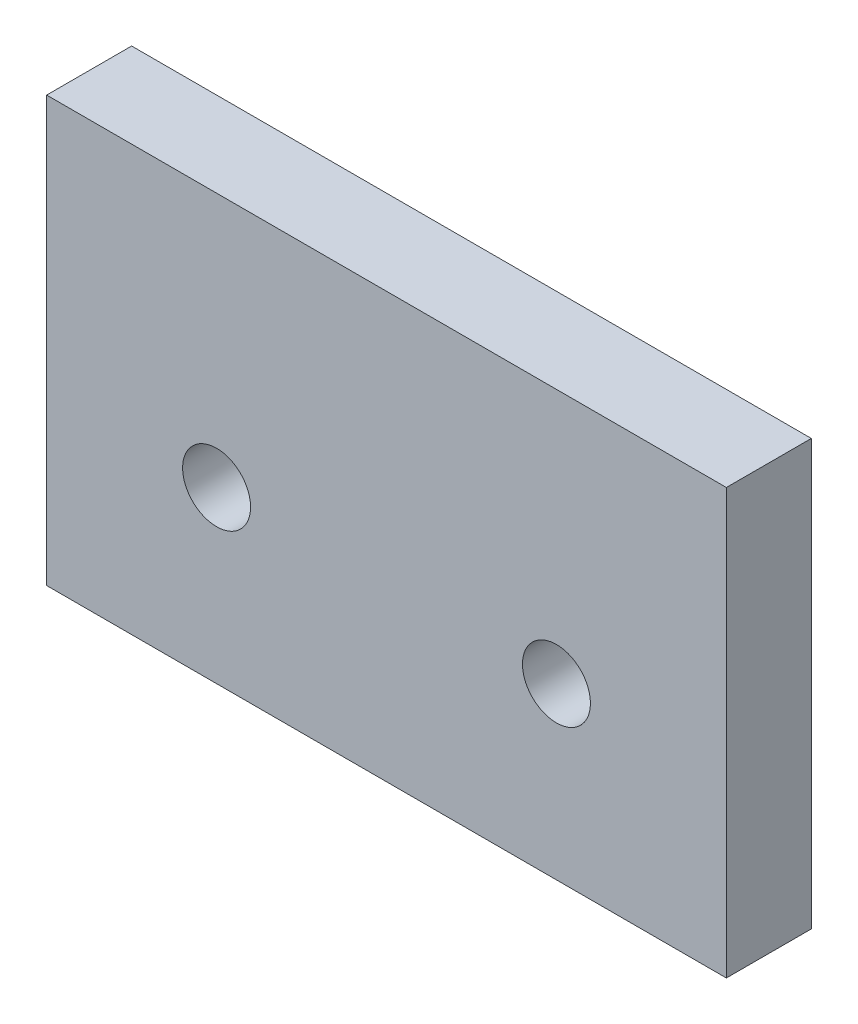
SolidWorks part; units mm, degrees
ref_plane "Front Plane" through (0, 0, 0) normal (0, 0, 1) x (1, 0, 0)
ref_plane "Top Plane" through (0, 0, 0) normal (0, 1, 0) x (1, 0, 0)
ref_plane "Right Plane" through (0, 0, 0) normal (1, 0, 0) x (0, 0, -1)
sketch "Sketch1" plane through (0, 0, 0) normal (1, 0, 0) x (0, 0, -1)
  line L0 (0, 0) -> (0, 12.7)
  line L1 (0, 0) -> (10.668, 0)
  line L2 (-3.175, -3.175) -> (10.668, -3.175)
  line L3 (-3.175, -3.175) -> (-3.175, 12.7)
  line L4 (-3.175, 12.7) -> (0, 12.7)
  line L5 (10.668, 0) -> (10.668, -3.175)
  dimension "D1" = 12.7
  dimension "D2" = 10.668
  dimension "D3" = 3.175
extrude "Boss-Extrude1" add sketch "Sketch1" along normal blind 25.4
sketch "Sketch2" plane through (0, 0, 3.175) normal (0, 0, 1) x (1, 0, 0)
  line L0 (25.4, 12.7) -> (25.4, -3.175) construction
  line L1 (25.4, 0) -> (0, 0) construction
  line L2 (25.4, 0) -> (0, 0) construction
  line L3 (0, 12.7) -> (0, -3.175) construction
  circle A0 centre (6.35, 3.175) radius 1.27
  circle A1 centre (19.05, 3.175) radius 1.27
  dimension "D2" = 2.54
  dimension "D4" = 2.54
  dimension "D1" = 6.35
  dimension "D3" = 3.175
  dimension "D5" = 3.175
  dimension "D6" = 6.35
extrude "Cut-Extrude1" cut sketch "Sketch2" against normal blind 25.4
sketch "Sketch3" plane through (0, 0, -10.668) normal (0, 0, -1) x (-1, 0, 0)
  line L4 (0, -3.175) -> (0, 0)
  line L5 (0, 0) -> (-25.4, 0)
  line L6 (-25.4, 0) -> (-25.4, -3.175)
  line L7 (-25.4, -3.175) -> (0, -3.175)
  line L8 (0, -3.175) -> (0, 0)
  line L9 (0, 0) -> (-25.4, 0)
  line L10 (-25.4, 0) -> (-25.4, -3.175)
  line L11 (-25.4, -3.175) -> (0, -3.175)
  dimension "D1" = 0
extrude "Cut-Extrude2" cut sketch "Sketch3" against normal up to surface (10.668 mm away) up to face at (7.62, 3.175, 0)
